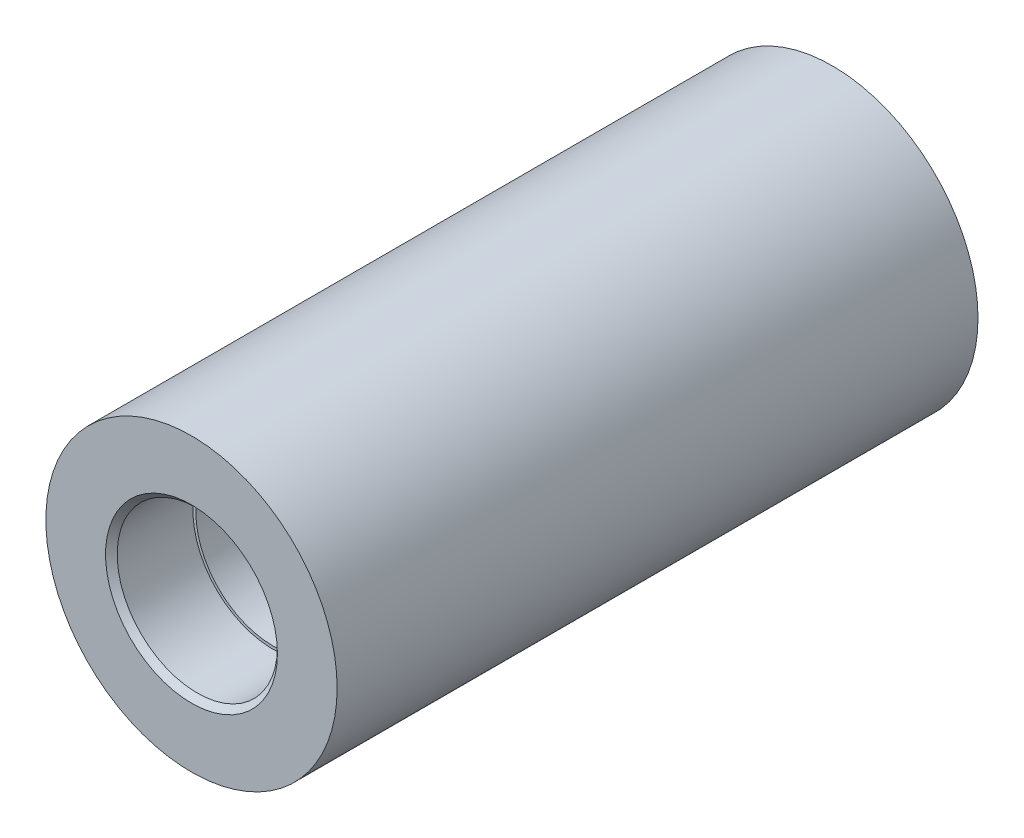
SolidWorks part; units mm, degrees
ref_plane "Ebene vorne" through (0, 0, 0) normal (0, 0, 1) x (1, 0, 0)
ref_plane "Ebene oben" through (0, 0, 0) normal (0, 1, 0) x (1, 0, 0)
ref_plane "Ebene rechts" through (0, 0, 0) normal (1, 0, 0) x (0, 0, -1)
sketch "Skizze1" plane through (0, 0, 0) normal (0, 0, 1) x (1, 0, 0)
  circle A0 centre (0, 0) radius 10
  circle A1 centre (0, 0) radius 5.3
  dimension "D1" = 20
  dimension "D2" = 10.6
extrude "Aufsatz-Linear austragen1" add sketch "Skizze1" along normal blind 44
sketch "Skizze2" plane through (0, 0, 44) normal (0, 0, 1) x (1, 0, 0)
  circle A0 centre (0, 0) radius 5.5
  dimension "D1" = 11
extrude "Schnitt-Linear austragen1" cut sketch "Skizze2" against normal blind 5.6
sketch "Skizze3" plane through (0, 0, 0) normal (0, 0, -1) x (-1, 0, 0)
  circle A0 centre (0, 0) radius 5.895
  dimension "D1" = 11.79
extrude "Schnitt-Linear austragen2" cut sketch "Skizze3" against normal blind 5.6
chamfer "Fase1" distance 0.4 angle 45 2 edges at (5.5, 0, 44) (-5.895, 0, 0)
